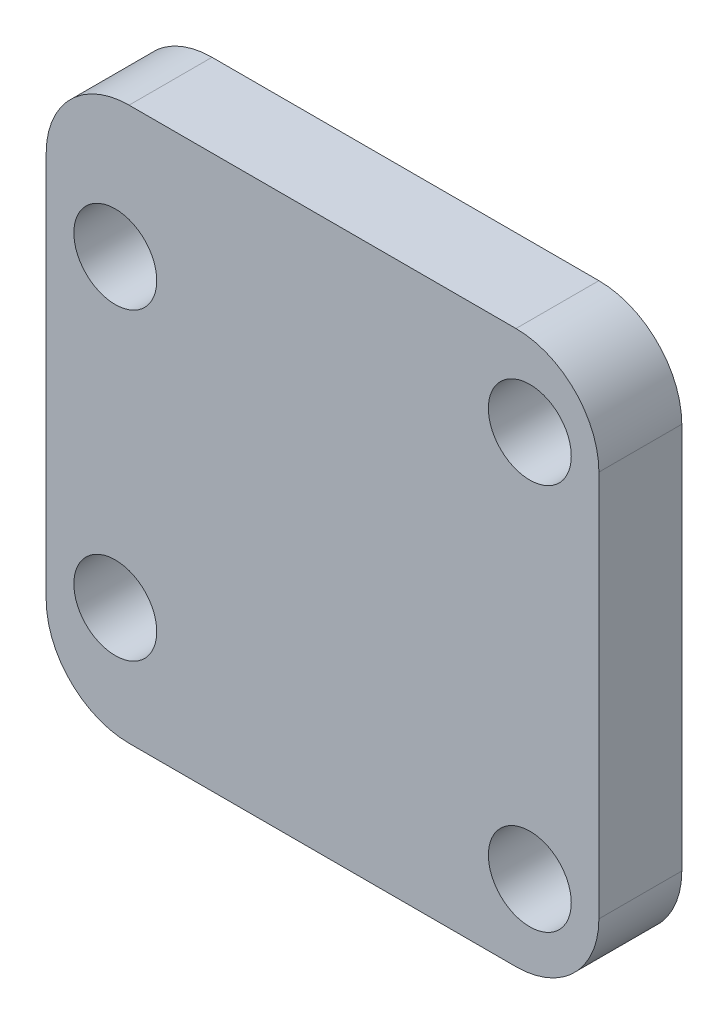
SolidWorks part; units mm, degrees
material "Thornel Mat VMA"
ref_plane "前视基准面" through (0, 0, 0) normal (0, 0, 1) x (1, 0, 0)
ref_plane "上视基准面" through (0, 0, 0) normal (0, 1, 0) x (1, 0, 0)
ref_plane "右视基准面" through (0, 0, 0) normal (1, 0, 0) x (0, 0, -1)
other "Configuration Table"
sketch "草图1" plane through (0, 0, 0) normal (0, 0, 1) x (1, 0, 0)
  line L0 (0, 0) -> (0, 20.6677) construction
  line L1 (-10, -10) -> (10, -10)
  line L2 (-10, -10) -> (-10, 10)
  line L3 (-10, 10) -> (10, 10)
  line L4 (10, -10) -> (10, 10)
  line L5 (-10, -10) -> (10, 10) construction
  line L6 (-10, 10) -> (10, -10) construction
  line L7 (0, 0) -> (20.7935, 0) construction
  circle A0 centre (7.5, 7) radius 1.5
  circle A1 centre (7.5, -7) radius 1.5
  circle A2 centre (-7.5, 5) radius 1.5
  circle A3 centre (-7.5, -6) radius 1.5
  point P0 (0, 0)
  dimension "D3" = 3
  dimension "D4" = 3
  dimension "D9" = 7.5
  dimension "D13" = 3
  dimension "D14" = 3
  dimension "D1" = 20
  dimension "D2" = 20
  dimension "D5" = 7
  dimension "D6" = 7
  dimension "D7" = 7.5
  dimension "D8" = 7.5
  dimension "D10" = 5
  dimension "D11" = 6
  dimension "D12" = 7.5
extrude "凸台-拉伸1" add sketch "草图1" along normal blind 3
fillet "圆角1" radius 3 4 edges at (10, -10, 1.5) (-10, -10, 1.5) (-10, 10, 1.5) (10, 10, 1.5)
